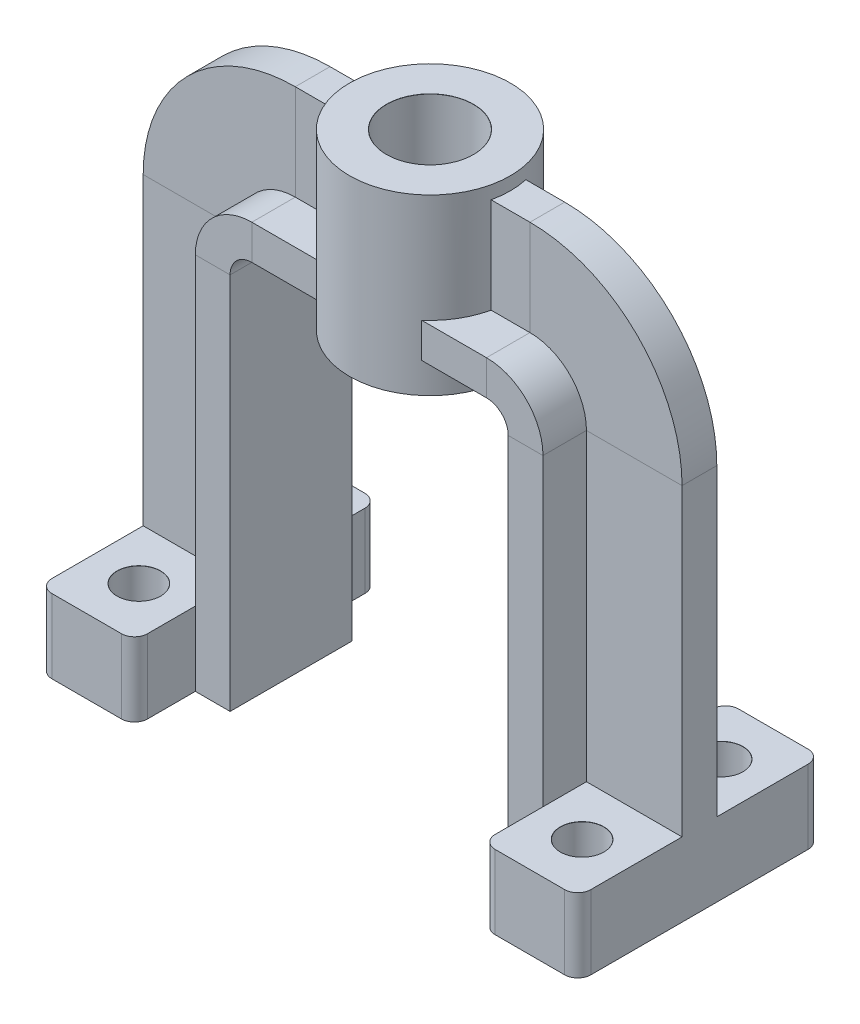
SolidWorks part; units mm, degrees
ref_plane "Front Plane" through (0, 0, 0) normal (0, 0, 1) x (1, 0, 0)
ref_plane "Top Plane" through (0, 0, 0) normal (0, 1, 0) x (1, 0, 0)
ref_plane "Right Plane" through (0, 0, 0) normal (1, 0, 0) x (0, 0, -1)
sketch "Sketch1" plane through (0, 0, 0) normal (0, 1, 0) x (1, 0, 0)
  line L0 (0, 0) -> (-32, 0) construction
  line L1 (-32, 14) -> (-32, -14)
  line L2 (-32, -14) -> (-40, -14)
  line L3 (-40, -14) -> (-40, -4)
  line L4 (-40, -4) -> (-62, -4)
  line L5 (-62, -4) -> (-62, 4)
  line L6 (-62, 4) -> (-40, 4)
  line L7 (-32, 14) -> (-40, 14)
  line L8 (-40, 14) -> (-40, 4)
  point P5 (0, 0)
  point P12 (-40, -4.8248)
  dimension "D1" = 8
  dimension "D2" = 8
  dimension "D3" = 30
  dimension "D4" = 28
  dimension "D5" = 32
sketch "Sketch2" plane through (0, 0, 0) normal (0, 0, 1) x (1, 0, 0)
  line L0 (-32, 0) -> (-32, 87)
  line L1 (-27, 92) -> (0, 92)
  arc A0 (-32, 87) -> (-27, 92) centre (-27, 87) cw
  dimension "D1" = 5
  dimension "D2" = 92
sweep "Sweep1" add profiles "Sketch1" path "Sketch2"
sketch "Sketch5" plane through (-62, 0, 0) normal (-1, 0, 0) x (0, 0, 1)
  line L1 (-28, 0) -> (28, 0)
  line L2 (-28, 0) -> (-28, 17)
  line L3 (-28, 17) -> (28, 17)
  line L4 (28, 0) -> (28, 17)
  point P4 (0, 0)
  dimension "D1" = 56
  dimension "D2" = 17
extrude "Boss-Extrude1" add sketch "Sketch5" against normal blind 22 contours L3 L4 L1 L2
hole_wizard "Ø10.0 (10) Diameter Hole1" positions "3DSketch1" profile "Sketch7" hole size "Ø10.0" standard "ANSI Metric" end condition through all
sketch3d "3DSketch1"
  line L1 (-62, 17, 4) -> (-62, 17, 28) construction
  line L3 (-40, 17, 28) -> (-62, 17, 28) construction
  point P0 (-51, 17, 16)
  point P2 (-51, 17, 16)
  dimension "D1" = 11
  dimension "D2" = 12
sketch "Sketch7" plane through (-51, 17, 16) normal (1, 0, 0) x (0, 0, 1)
  line L0 (0, 0) -> (0, 17)
  line L1 (0, 17) -> (5, 17)
  line L2 (5, 17) -> (5, 0.025)
  line L3 (5, 0.025) -> (5.025, 0)
  line L5 (5.025, 0) -> (0, 0)
  line L6 (-5, 0.025) -> (-5.025, 0) construction
  line L11 (0, -6.35) -> (0, 107.95) construction
  dimension "Thru Hole Dia." = 10
  dimension "Thru Hole Depth" = 17
  dimension "Near C'Sink Dia." = 10.05
  dimension "Near C'Sink Angle" = 90
mirror "Mirror1" about plane through (0, 0, 0) normal (0, 0, 1) of "Ø10.0 (10) Diameter Hole1"
fillet "Fillet1" radius 3 4 edges at (-40, 8.5, -28) (-62, 8.5, -28) (-40, 8.5, 28) (-62, 8.5, 28)
mirror "Mirror2" about plane through (0, 0, 0) normal (1, 0, 0) of bodies 104
ref_plane "Plane5" through (0, 125, 0) normal (0, 1, 0) x (1, 0, 0)
sketch "Sketch10" plane through (0, 125, 0) normal (0, 1, 0) x (1, 0, 0)
  circle A0 centre (0, 0) radius 18.5
  dimension "D1" = 37
extrude "Boss-Extrude2" add sketch "Sketch10" against normal blind 40 contours A0
hole_wizard "Ø20.0 (20) Diameter Hole1" positions "3DSketch2" profile "Sketch11" hole size "Ø20.0" standard "ANSI Metric" end condition up to next
sketch3d "3DSketch2"
  circle A0 centre (0, 125, 0) radius 18.5 construction
  point P0 (0, 125, 0)
  point P5 (0, 143.5, 0)
sketch "Sketch11" plane through (0, 125, 0) normal (1, 0, 0) x (0, 0, 1)
  line L0 (0, 0) -> (0, 40)
  line L1 (0, 40) -> (10, 40)
  line L2 (10, 40) -> (10, 0.025)
  line L3 (10, 0.025) -> (10.025, 0)
  line L5 (10.025, 0) -> (0, 0)
  line L6 (-10, 0.025) -> (-10.025, 0) construction
  line L11 (0, -6.35) -> (0, 107.95) construction
  dimension "Thru Hole Dia." = 20
  dimension "Thru Hole Depth" = 40
  dimension "Near C'Sink Dia." = 20.05
  dimension "Near C'Sink Angle" = 90
